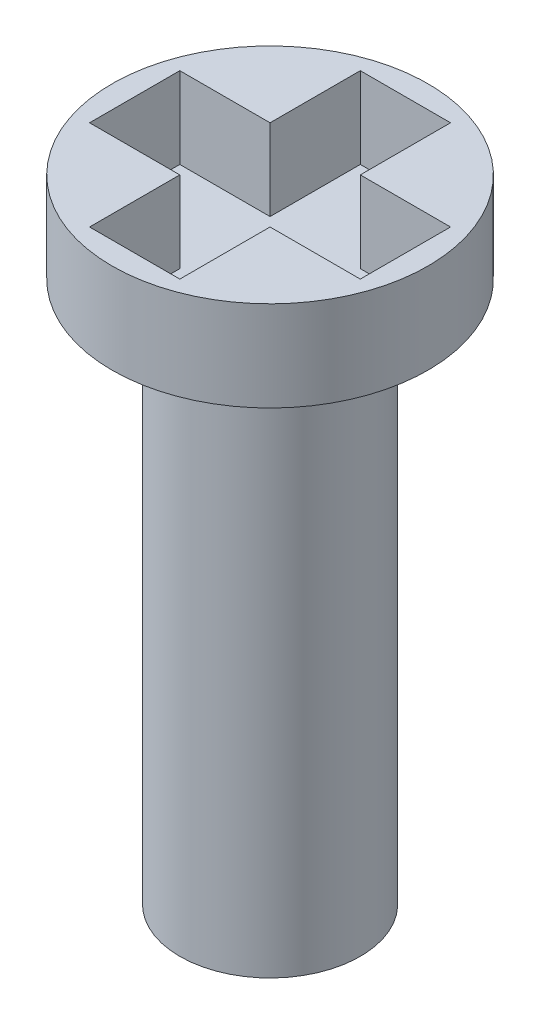
SolidWorks part; units mm, degrees
material "Plain Carbon Steel"
ref_plane "Front Plane" through (0, 0, 0) normal (0, 0, 1) x (1, 0, 0)
ref_plane "Top Plane" through (0, 0, 0) normal (0, 1, 0) x (1, 0, 0)
ref_plane "Right Plane" through (0, 0, 0) normal (1, 0, 0) x (0, 0, -1)
sketch "Sketch1" plane through (0, 0, 0) normal (0, 1, 0) x (1, 0, 0)
  line L1 (-1.5, -0.5) -> (1.5, -0.5)
  line L2 (-1.5, -0.5) -> (-1.5, 0.5)
  line L3 (-1.5, 0.5) -> (1.5, 0.5)
  line L4 (1.5, -0.5) -> (1.5, 0.5)
  line L5 (-1.5, -0.5) -> (1.5, 0.5) construction
  line L6 (-1.5, 0.5) -> (1.5, -0.5) construction
  line L7 (0.5, -1.5) -> (-0.5, -1.5)
  line L8 (0.5, -1.5) -> (0.5, 1.5)
  line L9 (0.5, 1.5) -> (-0.5, 1.5)
  line L10 (-0.5, -1.5) -> (-0.5, 1.5)
  line L11 (0.5, -1.5) -> (-0.5, 1.5) construction
  line L12 (0.5, 1.5) -> (-0.5, -1.5) construction
  circle A0 centre (0, 0) radius 1.75
  dimension "D1" = 3.5
  dimension "D2" = 1
  dimension "D3" = 3
extrude "Boss-Extrude1" add sketch "Sketch1" along normal blind 1 contours A0 L7 L10 L1 L2 L3 L9 L8 L4
sketch "Sketch2" plane through (0, 0, 0) normal (0, -1, 0) x (1, 0, 0)
  circle A1 centre (0, 0) radius 1.75
  circle A2 centre (0, 0) radius 1.75
  dimension "D1" = 0
extrude "Boss-Extrude2" add sketch "Sketch2" against normal blind 0.1
sketch "Sketch3" plane through (0, 0, 0) normal (0, -1, 0) x (1, 0, 0)
  circle A0 centre (0, 0) radius 1
  dimension "D1" = 2
extrude "Boss-Extrude3" add sketch "Sketch3" along normal blind 6
